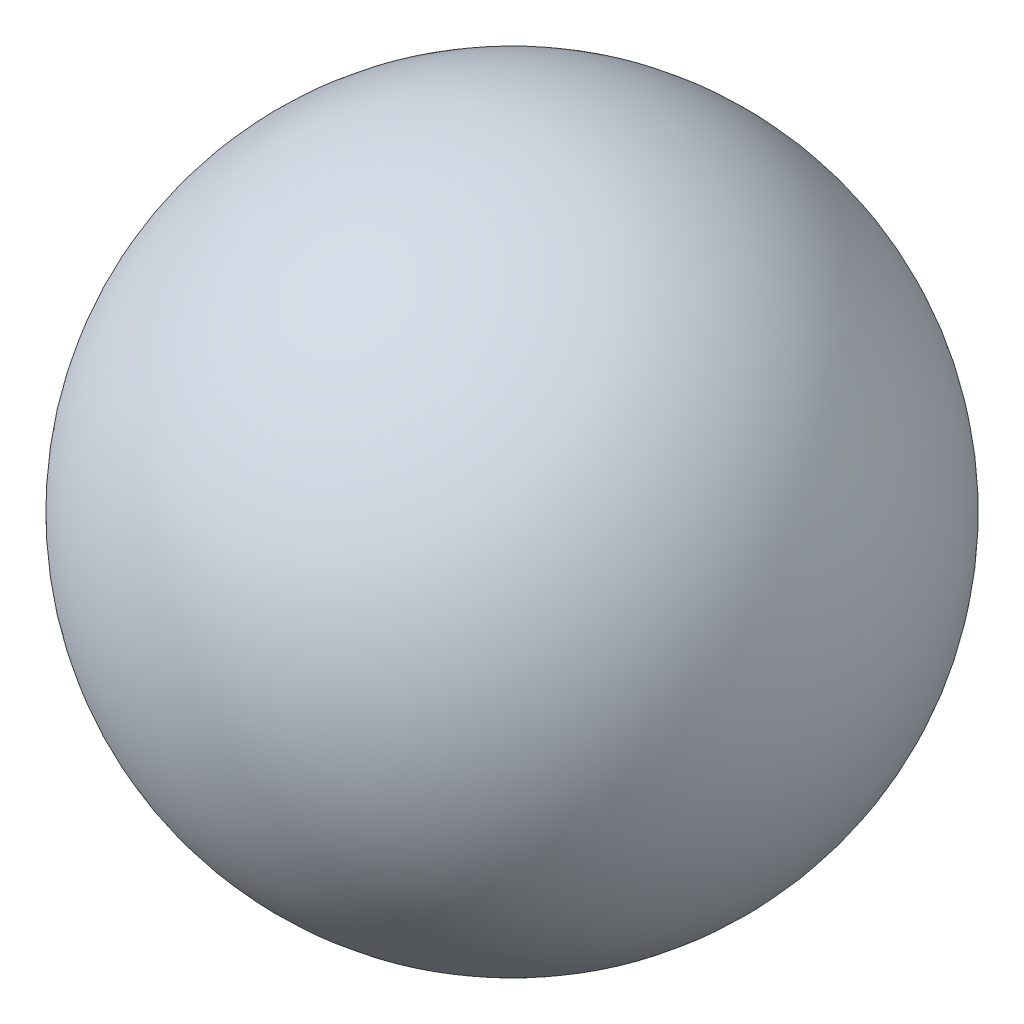
SolidWorks part; units mm, degrees
ref_plane "Front Plane" through (0, 0, 0) normal (0, 0, 1) x (1, 0, 0)
ref_plane "Top Plane" through (0, 0, 0) normal (0, 1, 0) x (1, 0, 0)
ref_plane "Right Plane" through (0, 0, 0) normal (1, 0, 0) x (0, 0, -1)
sketch "Sketch1" plane through (0, 0, 0) normal (0, 0, 1) x (1, 0, 0)
  line L0 (0, 4.5242) -> (0, -4.5242) construction
  line L1 (0, 4.5242) -> (0, -4.5242)
  line L2 (-28.9535, 4.5242) -> (-28.9535, -4.5242) construction
  arc A0 (0, -4.5242) -> (0, 4.5242) centre (0, 0) ccw
revolve "Revolve1" add sketch "Sketch1" angle 360 about L0
